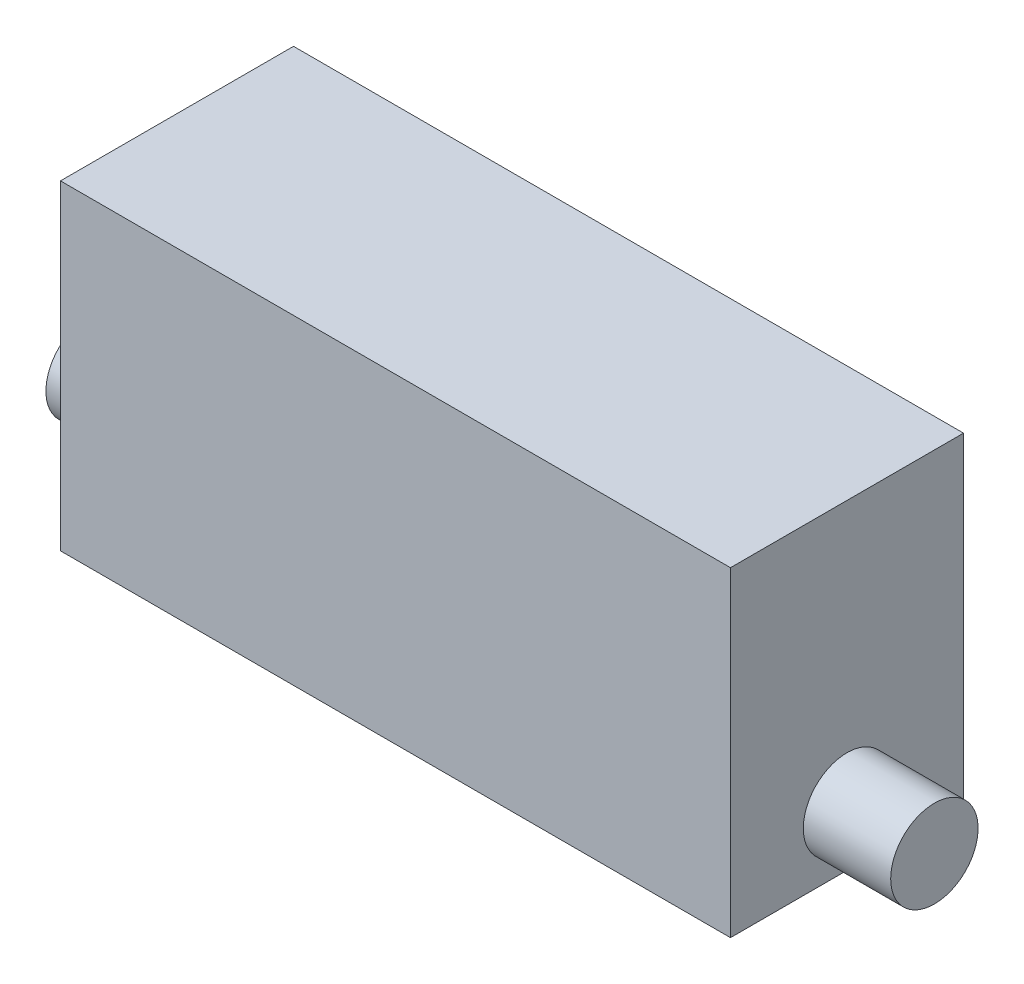
SolidWorks part; units mm, degrees
ref_plane "Front Plane" through (0, 0, 0) normal (0, 0, 1) x (1, 0, 0)
ref_plane "Top Plane" through (0, 0, 0) normal (0, 1, 0) x (1, 0, 0)
ref_plane "Right Plane" through (0, 0, 0) normal (1, 0, 0) x (0, 0, -1)
sketch "Sketch1" plane through (0, 0, 0) normal (0, 1, 0) x (1, 0, 0)
  line L1 (0, 0) -> (146.05, 0)
  line L2 (0, 0) -> (0, 50.8)
  line L3 (0, 50.8) -> (146.05, 50.8)
  line L4 (146.05, 0) -> (146.05, 50.8)
  dimension "D1" = 50.8
  dimension "D2" = 146.05
extrude "Boss-Extrude1" add sketch "Sketch1" along normal blind 69.85
sketch "Sketch2" plane through (146.05, 0, 0) normal (1, 0, 0) x (0, 0, -1)
  line L0 (0, 69.85) -> (0, 0) construction
  line L2 (0, 69.85) -> (50.8, 69.85) construction
  circle A0 centre (25.4, 12.7) radius 9.525
  dimension "D3" = 19.05
  dimension "D1" = 25.4
  dimension "D2" = 57.15
extrude "Boss-Extrude2" add sketch "Sketch2" along normal blind 19.05
sketch "Sketch3" plane through (0, 0, 0) normal (-1, 0, 0) x (0, 0, 1)
  line L0 (-50.8, 69.85) -> (-50.8, 0) construction
  line L2 (-50.8, 69.85) -> (0, 69.85) construction
  circle A0 centre (-25.4, 12.7) radius 9.525
  point P7 (-25.4, 69.85)
  dimension "D3" = 19.05
  dimension "D1" = 25.4
  dimension "D2" = 57.15
extrude "Boss-Extrude3" add sketch "Sketch3" along normal blind 19.05
